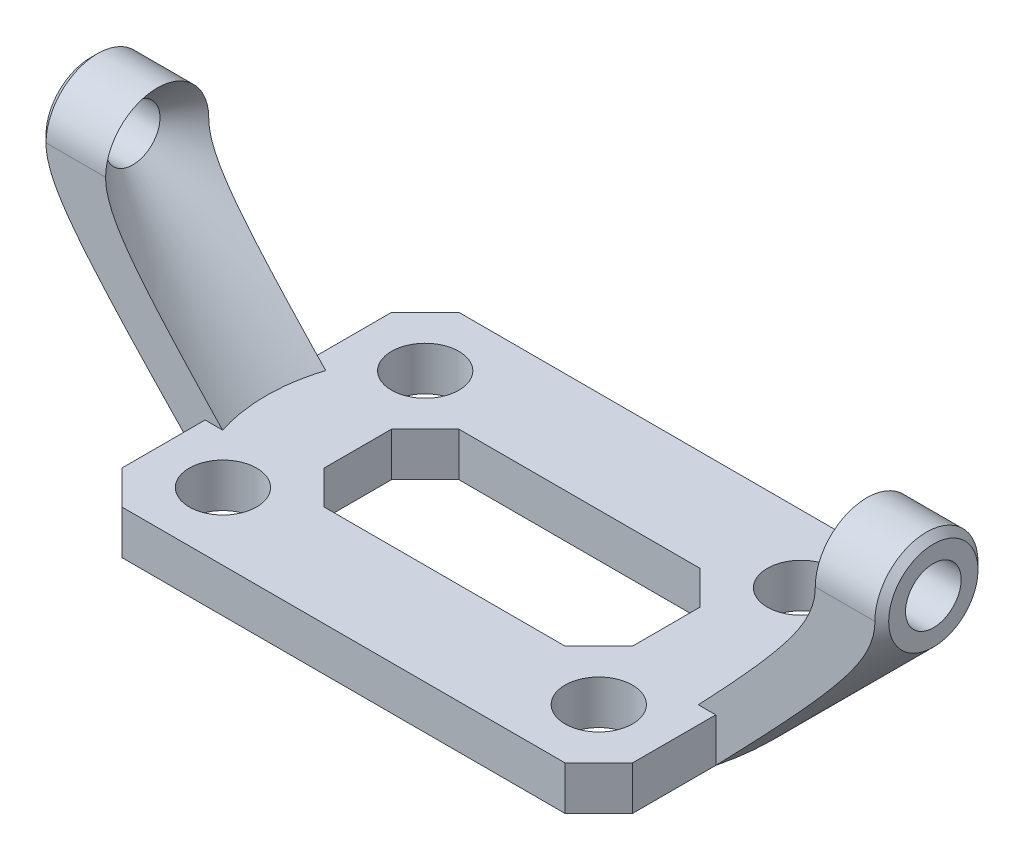
SolidWorks part; units mm, degrees
ref_plane "Front Plane" through (0, 0, 0) normal (0, 0, 1) x (1, 0, 0)
ref_plane "Top Plane" through (0, 0, 0) normal (0, 1, 0) x (1, 0, 0)
ref_plane "Right Plane" through (0, 0, 0) normal (1, 0, 0) x (0, 0, -1)
sketch "Sketch1" plane through (0, 0, 0) normal (0, 0, 1) x (1, 0, 0)
  line L0 (15.15, 0) -> (25, 9.85)
  line L1 (25, 9.85) -> (25, 10.85)
  line L2 (25, 10.85) -> (22.5, 10.85)
  line L3 (22.5, 10.85) -> (22.5, 10.8855)
  line L4 (22.5, 10.8855) -> (14.1145, 2.5)
  line L5 (14.1145, 2.5) -> (-14.1145, 2.5)
  line L6 (0, 2.5) -> (0, 0) construction
  line L7 (-15.15, 0) -> (15.15, 0)
  line L8 (14.1145, 2.5) -> (15.8822, 0.7322) construction
  line L9 (-0.0791, 12.5) -> (49999.9209, 12.5) construction
  line L10 (-14.1145, 2.5) -> (-15.8822, 0.7322) construction
  line L11 (-22.5, 10.8855) -> (-14.1145, 2.5)
  line L12 (-22.5, 10.85) -> (-22.5, 10.8855)
  line L13 (-25, 10.85) -> (-22.5, 10.85)
  line L14 (-25, 9.85) -> (-25, 10.85)
  line L15 (-15.15, 0) -> (-25, 9.85)
  dimension "D1" = 2.5
  dimension "D2" = 2.5
  dimension "D3" = 50
  dimension "D4" = 25
  dimension "D5" = 3.3
  dimension "D6" = 1
  dimension "D7" = 135
revolve "Revolve1" add sketch "Sketch1" angle 360 about L9
sketch "Sketch2" plane through (0, 0, 0) normal (1, 0, 0) x (0, 0, -1)
  line L0 (-2.65, 24.7159) -> (-2.65, 14.03) construction
  line L1 (2.65, 24.7159) -> (2.65, 14.03) construction
  line L2 (0, 12.5) -> (-2.65, 14.03) construction
  line L3 (0, 12.5) -> (2.65, 14.03) construction
  line L4 (-2.65, 14.03) -> (-11.9043, 8.687) construction
  line L5 (2.65, 14.03) -> (11.9043, 8.687) construction
  line L6 (-3.06, 12.5) -> (-3.06, 0.3803)
  line L7 (3.06, 12.5) -> (3.06, 0.3803)
  circle A0 centre (0, 12.5) radius 12.5 construction
  arc A1 (-11.9043, 8.687) -> (11.9043, 8.687) centre (0, 12.5) ccw construction
  arc A2 (-2.65, 24.7159) -> (2.65, 24.7159) centre (0, 12.5) cw construction
  circle A3 centre (0, 12.5) radius 2.65 construction
  arc A4 (2.65, 14.03) -> (-2.65, 14.03) centre (0, 12.5) ccw
  arc A5 (3.06, 12.5) -> (-3.06, 12.5) centre (0, 12.5) ccw
  arc A6 (-3.06, 0.3803) -> (3.06, 0.3803) centre (0, 12.5) ccw
  dimension "D1" = 120
  dimension "D2" = 120
extrude "Cut-Extrude1" cut sketch "Sketch2" against normal through all both and the other way through all flip side to cut contours L6 A6 L7 A5
ref_plane "Plane1" through (-14.1145, 0, 0) normal (1, 0, 0) x (0, 0, -1)
ref_plane "Plane2" through (14.1145, 0, 0) normal (1, 0, 0) x (0, 0, -1)
sketch "Sketch11" plane through (0, 0, 0) normal (0, 0, 1) x (1, 0, 0)
  line L0 (15.15, 2.9797) -> (-15.15, 2.9797)
  line L1 (15.15, 2.9797) -> (15.15, 0.3803)
  line L2 (15.15, 0.3803) -> (-15.15, 0.3803)
  line L3 (-15.15, 0.3803) -> (-15.15, 2.9797)
extrude "Boss-Extrude2" add sketch "Sketch11" along normal mid plane 20
sketch "Sketch12" plane through (-15.15, 0, 0) normal (-1, 0, 0) x (0, 0, 1)
  line L0 (-3.06, 0.3803) -> (3.06, 0.3803)
  arc A0 (-3.06, 0.3803) -> (3.06, 0.3803) centre (0, 12.5) ccw
  arc A1 (-3.06, 0.3803) -> (3.06, 0.3803) centre (0, 12.5) ccw construction
extrude "Cut-Extrude6" cut sketch "Sketch12" against normal through all both and the other way through all
sketch "Sketch13" plane through (0, 2.9797, 0) normal (0, 1, 0) x (1, 0, 0)
  line L10 (9.15, 4) -> (9.15, -4)
  line L11 (-9.15, 4) -> (-9.15, -4)
  line L13 (15.15, -10) -> (-15.15, -10) construction
  line L14 (15.15, -10) -> (15.15, -3.06) construction
  line L15 (0, 0) -> (0, -50000) construction
  line L16 (0, 0) -> (-50000, 0) construction
  line L22 (-9.15, -4) -> (9.15, -4)
  line L23 (9.15, 4) -> (-9.15, 4)
  dimension "D2" = 6
  dimension "D1" = 6
extrude "Cut-Extrude7" cut sketch "Sketch13" against normal through all
sketch "Sketch14" plane through (0, 2.9797, 0) normal (0, 1, 0) x (1, 0, 0)
  line L0 (15.15, -10) -> (-15.15, -10) construction
  line L1 (15.15, -10) -> (15.15, -3.06) construction
  line L2 (0, 0) -> (0, -50000) construction
  line L3 (0, 0) -> (50000, 0) construction
  circle A0 centre (11.15, -6) radius 2
  circle A1 centre (-11.15, -6) radius 2
  circle A2 centre (-11.15, 6) radius 2
  circle A3 centre (11.15, 6) radius 2
  dimension "D1" = 4
  dimension "D3" = 4
  dimension "D2" = 4
extrude "Cut-Extrude8" cut sketch "Sketch14" against normal through all
chamfer "Chamfer1" distance 2 angle 45 8 edges at (-15.15, 1.68, 10) (-15.15, 1.68, -10) (15.15, 1.68, -10) (15.15, 1.68, 10) (-9.15, 1.68, -4) (-9.15, 1.68, 4) (9.15, 1.68, -4) (9.15, 1.68, 4)
